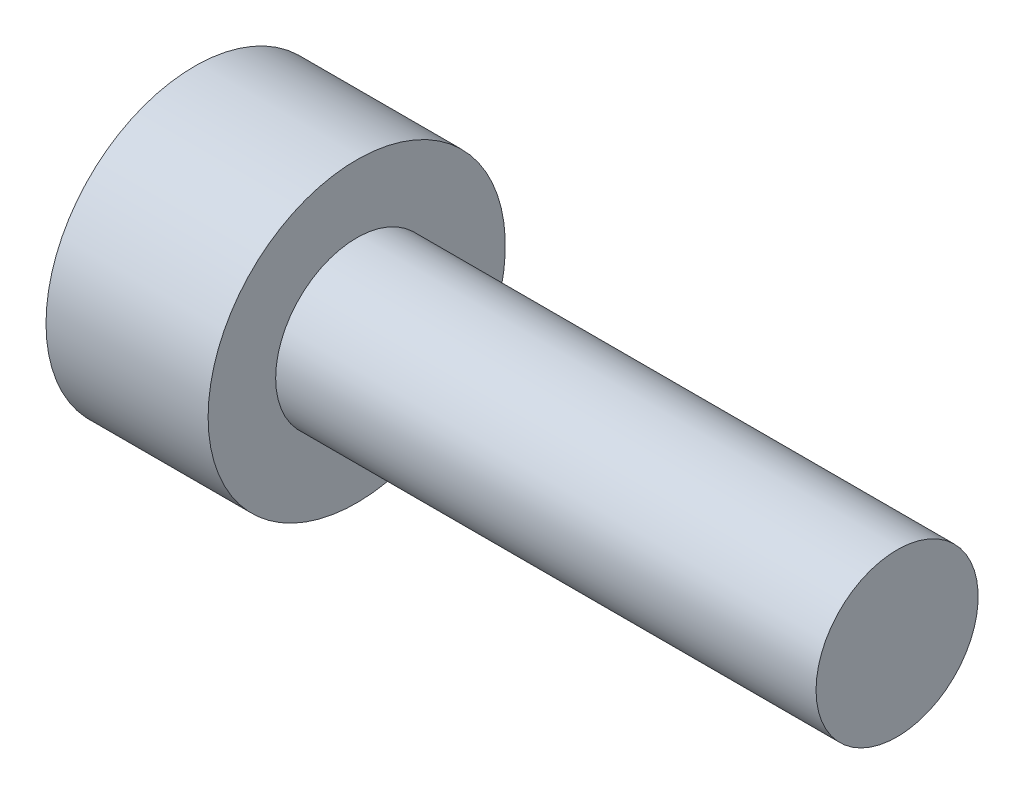
SolidWorks part; units mm, degrees
material "AISI Type 316L stainless steel"
ref_plane "Front Plane" through (0, 0, 0) normal (0, 0, 1) x (1, 0, 0)
ref_plane "Top Plane" through (0, 0, 0) normal (0, 1, 0) x (1, 0, 0)
ref_plane "Right Plane" through (0, 0, 0) normal (1, 0, 0) x (0, 0, -1)
sketch "Axial profile (mm)" plane through (0, 0, 0) normal (0, 0, 1) x (1, 0, 0)
  line L0 (-110, 0) -> (75, 0) construction
  line L1 (6.7, 0) -> (19.7, 0)
  line L2 (19.7, 0) -> (19.7, 1.5)
  line L3 (19.7, 1.5) -> (9.7, 1.5)
  line L4 (9.7, 1.5) -> (9.7, 2.75)
  line L5 (9.7, 2.75) -> (6.7, 2.75)
  line L6 (6.7, 2.75) -> (6.7, 0)
revolve "Full revolution" add sketch "Axial profile (mm)" angle 360 about L0
